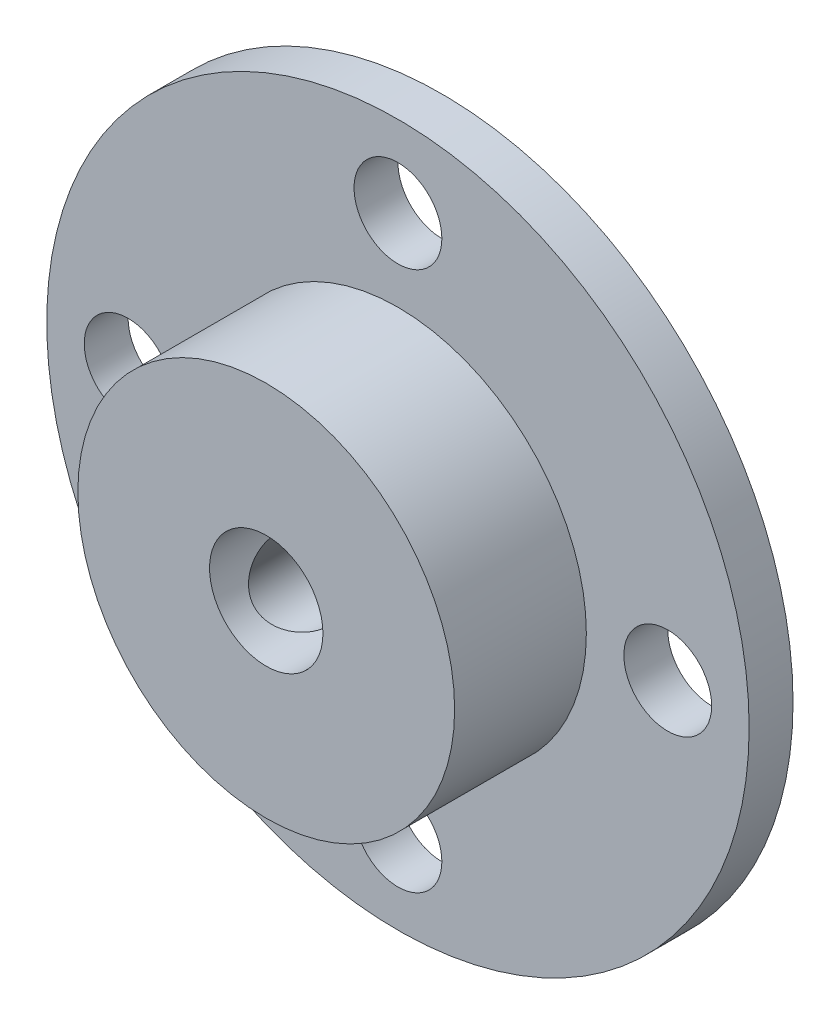
SolidWorks part; units mm, degrees
ref_plane "Front Plane" through (0, 0, 0) normal (0, 0, 1) x (1, 0, 0)
ref_plane "Top Plane" through (0, 0, 0) normal (0, 1, 0) x (1, 0, 0)
ref_plane "Right Plane" through (0, 0, 0) normal (1, 0, 0) x (0, 0, -1)
sketch "Sketch1" plane through (15.3043, 0, 0) normal (1, 0, 0) x (0, 0, -1)
  line L0 (-3.175, 27.8785) -> (-3.175, 21.5285) construction
  line L2 (-3.175, 22.6535) -> (-13.843, 22.6535) construction
  line L3 (-13.843, 26.7535) -> (-13.843, 22.6535) construction
  line L4 (-3.175, 27.8785) -> (-3.175, 21.5285)
  line L6 (-7.493, 22.6535) -> (-13.843, 22.6535)
  line L7 (-13.843, 26.7535) -> (-13.843, 22.6535)
  line L8 (-7.493, 45.8211) -> (-7.493, 3.5858) construction
  line L9 (-7.493, 26.7535) -> (-7.493, 24.7035)
  line L10 (-7.493, 12.0035) -> (-9.0805, 12.0035)
  line L11 (-9.0805, 12.0035) -> (-9.0805, 17.891)
  line L12 (-9.0805, 17.891) -> (-13.843, 17.891)
  line L13 (-13.843, 17.891) -> (-13.843, 22.6535)
  line L14 (-13.843, 24.7035) -> (-3.175, 24.7035) construction
  line L15 (-7.493, 22.6535) -> (-7.493, 12.0035)
  dimension "D1" = 12.7
  dimension "D2" = 1.5875
  dimension "D3" = 4.7625
revolve "Revolve1" add sketch "Sketch1" angle 360 about L14
hole_wizard "1/8 (0.125) Diameter Hole1" positions "Sketch2" profile "Sketch3" hole size "1/8" standard "ANSI Inch" end condition through all
sketch "Sketch2" plane through (0, 0, 9.0805) normal (0, 0, 1) x (1, 0, 0)
  line L0 (15.3043, 12.0035) -> (15.3043, 17.891) construction
  line L2 (8.4918, 24.7035) -> (2.6043, 24.7035) construction
  line L4 (22.1168, 24.7035) -> (28.0043, 24.7035) construction
  line L6 (15.3043, 31.516) -> (15.3043, 37.4035) construction
  circle A0 centre (15.3043, 24.7035) radius 6.8125 construction
  circle A1 centre (15.3043, 24.7035) radius 12.7 construction
  circle A2 centre (15.3043, 24.7035) radius 6.8125
  circle A3 centre (15.3043, 24.7035) radius 12.7
  point P0 (15.3043, 14.9472)
  point P2 (25.0606, 24.7035)
  point P4 (15.3043, 34.4597)
  point P6 (5.5481, 24.7035)
sketch "Sketch3" plane through (15.3043, 14.9472, 9.0805) normal (1, 0, 0) x (0, -1, 0)
  line L0 (0, 0) -> (0, 1.5875)
  line L1 (0, 1.5875) -> (1.5875, 1.5875)
  line L2 (1.5875, 1.5875) -> (1.5875, 0)
  line L5 (1.5875, 0) -> (0, 0)
  line L11 (0, -6.35) -> (0, 107.95) construction
  dimension "Thru Hole Dia." = 3.175
  dimension "Thru Hole Depth" = 1.5875
ref_plane "Plane1" through (15.1867, 15.1867, 0) normal (-0.7071, -0.7071, 0) x (0, 0, 1)
hole_wizard "#6-32 Tapped Hole1" positions "Sketch4" profile "Sketch5" tap size "#6-32" standard "ANSI Inch"
sketch "Sketch4" plane through (15.1867, 15.1867, 0) normal (-0.7071, -0.7071, 0) x (0, 0, 1)
  line L0 (13.843, -0.1663) -> (13.843, 13.4587) construction
  line L1 (9.0805, -0.1663) -> (9.0805, 13.4587) construction
  line L3 (9.0805, -0.1663) -> (9.0805, 13.4587)
  line L4 (9.0805, 6.6462) -> (13.843, 6.6462) construction
  line L6 (9.0805, -0.1663) -> (9.0805, 13.4587)
  line L7 (13.843, -0.1663) -> (13.843, 13.4587)
  point P0 (11.4618, 6.6462)
  point P11 (11.4618, 6.6462)
  point P14 (13.843, 6.6462)
sketch "Sketch5" plane through (10.4872, 19.8863, 11.4618) normal (0, 0, 1) x (0.7071, -0.7071, 0)
  line L0 (0, 0) -> (0, 7.6707)
  line L1 (0, 7.6707) -> (1.3525, 6.858)
  line L2 (1.3525, 6.858) -> (1.3525, 0)
  line L5 (1.3525, 0) -> (0, 0)
  line L10 (0, 7.6707) -> (-1.3526, 6.858) construction
  line L11 (0, -6.35) -> (0, 107.95) construction
  dimension "Tap Drill Dia." = 2.7051
  dimension "Tap Drill Depth" = 6.858
  dimension "Drill Angle" = 118
cosmetic thread "Hole Thread2" parameters "D1"=5.272, "D2"=3.5052
